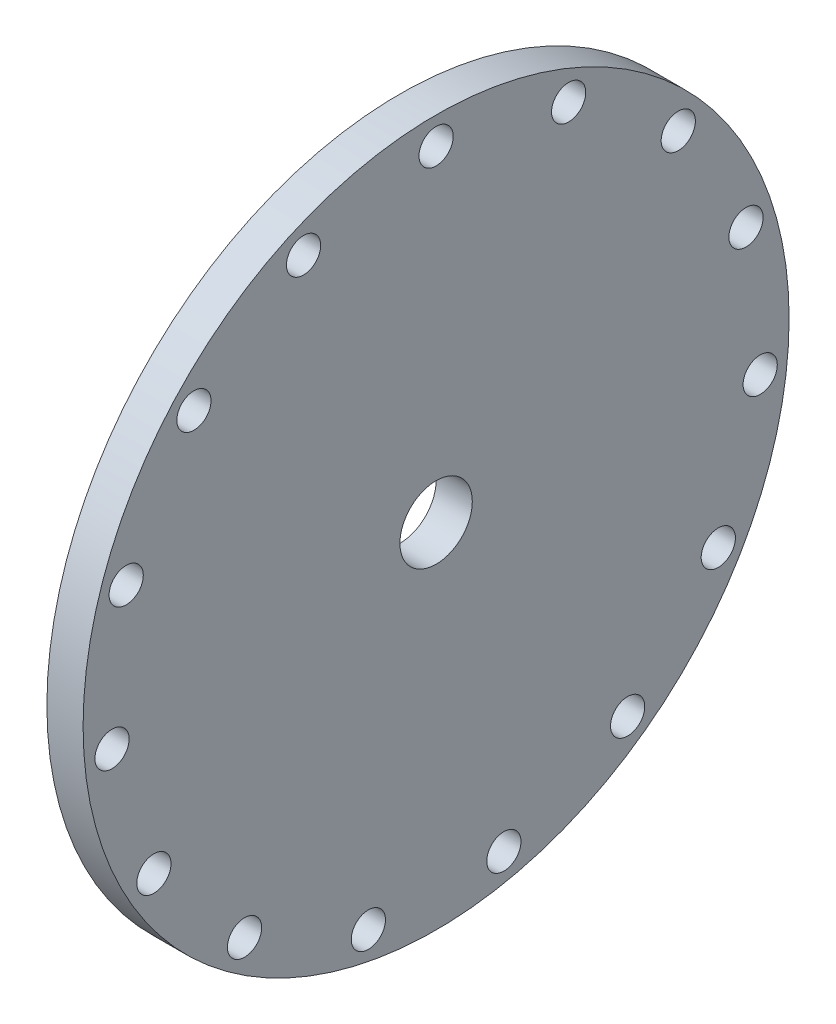
SolidWorks part; units mm, degrees
ref_plane "Front Plane" through (0, 0, 0) normal (0, 0, 1) x (1, 0, 0)
ref_plane "Top Plane" through (0, 0, 0) normal (0, 1, 0) x (1, 0, 0)
ref_plane "Right Plane" through (0, 0, 0) normal (1, 0, 0) x (0, 0, -1)
sketch "Sketch1" plane through (0, 0, 0) normal (1, 0, 0) x (0, 0, -1)
  circle A0 centre (0, 0) radius 30.9562
  circle A1 centre (0, 0) radius 28.575 construction
  circle A2 centre (0, 28.575) radius 1.5
  circle A3 centre (11.6225, 26.1046) radius 1.5
  circle A4 centre (21.2354, 19.1204) radius 1.5
  circle A5 centre (27.1764, 8.8302) radius 1.5
  circle A6 centre (28.4185, -2.9869) radius 1.5
  circle A7 centre (24.7467, -14.2875) radius 1.5
  circle A8 centre (16.796, -23.1177) radius 1.5
  circle A9 centre (5.9411, -27.9506) radius 1.5
  circle A10 centre (-5.9411, -27.9506) radius 1.5
  circle A11 centre (-16.796, -23.1177) radius 1.5
  circle A12 centre (-24.7467, -14.2875) radius 1.5
  circle A13 centre (-28.4185, -2.9869) radius 1.5
  circle A14 centre (-27.1764, 8.8302) radius 1.5
  circle A15 centre (-21.2354, 19.1204) radius 1.5
  circle A16 centre (-11.6225, 26.1046) radius 1.5
  dimension "D1" = 15
  dimension "D2" = 61.9125
  dimension "D3" = 3
  dimension "D4" = 57.15
extrude "Boss-Extrude1" add sketch "Sketch1" along normal blind 3.175
sketch "Sketch2" plane through (3.175, 0, 0) normal (1, 0, 0) x (0, 0, -1)
  circle A0 centre (0, 0) radius 3.175
  dimension "D1" = 6.35
extrude "Cut-Extrude1" cut sketch "Sketch2" against normal through all
sketch "Sketch3" plane through (3.175, 0, 0) normal (1, 0, 0) x (0, 0, -1)
  circle A0 centre (0, 0) radius 28.575 construction
  point P0 (0, 0)
